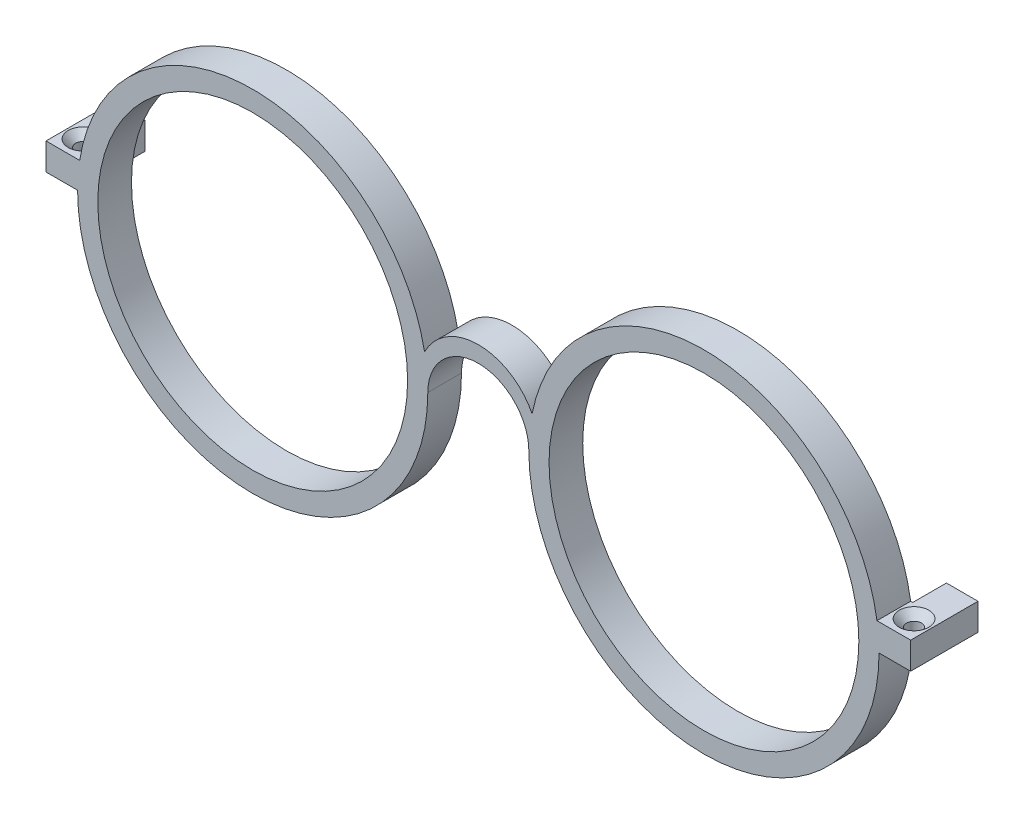
SolidWorks part; units mm, degrees
ref_plane "Ebene vorne" through (0, 0, 0) normal (0, 0, 1) x (1, 0, 0)
ref_plane "Ebene oben" through (0, 0, 0) normal (0, 1, 0) x (1, 0, 0)
ref_plane "Ebene rechts" through (0, 0, 0) normal (1, 0, 0) x (0, 0, -1)
sketch "Skizze1" plane through (0, 0, 0) normal (0, 0, 1) x (1, 0, 0)
  line L0 (59.5, 0) -> (64.1905, 0)
  line L1 (64.1905, 0) -> (64.1905, 4)
  line L2 (64.1905, 4) -> (59.1905, 4)
  line L3 (-59.5, 0) -> (-64.1905, 0)
  line L4 (-64.1905, 0) -> (-64.1905, 4)
  line L5 (-64.1905, 4) -> (-59.1905, 4)
  circle A0 centre (-33.5, 0) radius 26
  circle A1 centre (33.5, 0) radius 26
  arc A2 (-7.5, 0) -> (7.5, 0) centre (0, 0) cw
  circle A3 centre (33.5, 0) radius 23
  circle A4 centre (-33.5, 0) radius 23
  arc A5 (-7.9808, 4.9768) -> (7.9853, 5) centre (0.0081, 0.9725) cw
  dimension "D1" = 52
  dimension "D2" = 52
  dimension "D5" = 7.5
  dimension "D6" = 46
  dimension "D7" = 46
  dimension "D3" = 33.5
  dimension "D4" = 33.5
  dimension "D8" = 5
  dimension "D9" = 5
  dimension "D10" = 4
  dimension "D11" = 4
  dimension "D12" = 5
  dimension "D13" = 5
extrude "Aufsatz-Linear austragen1" add sketch "Skizze1" along normal blind 5 contours A0 A4 | A0 L5 L4 L3 | A4 | A5 A0 A2 A1 | A1 A3 | A1 L0 L1 L2
sketch "Skizze2" plane through (0, 0, 0) normal (0, 0, -1) x (-1, 0, 0)
  line L1 (-64.1905, 4) -> (-59.5, 4)
  line L2 (-64.1905, 4) -> (-64.1905, 0)
  line L3 (-64.1905, 0) -> (-59.5, 0)
  line L4 (-59.5, 4) -> (-59.5, 0)
  line L5 (64.1905, 4) -> (59.5, 4)
  line L6 (64.1905, 4) -> (64.1905, 0)
  line L7 (64.1905, 0) -> (59.5, 0)
  line L8 (59.5, 4) -> (59.5, 0)
extrude "Aufsatz-Linear austragen2" add sketch "Skizze2" along normal blind 5
hole_wizard "Formsenkung für M2 Senkschraube mit Schlitz/Kreuzschlitz1" positions "Skizze5" profile "Skizze3" countersink size "M2" standard "ANSI Metrisch"
sketch "Skizze5" plane through (0, 4, 0) normal (0, 1, 0) x (1, 0, 0)
  line L0 (-64.1905, -5) -> (-59.1905, -5) construction
  line L1 (-64.1905, -5) -> (-64.1905, 5) construction
  line L2 (64.1905, -5) -> (64.1905, 5) construction
  line L3 (64.1905, -5) -> (59.1905, -5) construction
  point P0 (61.6905, -2)
  point P2 (-61.6905, -2)
  point P21 (61.6905, -5)
  dimension "D1" = 3
  dimension "D2" = 2.5
  dimension "D3" = 2.5
  dimension "D4" = 3
sketch "Skizze3" plane through (61.6905, 4, 2) normal (1, 0, 0) x (0, 0, 1)
  line L0 (0, 0) -> (0, 50.6609)
  line L1 (0, 50.6609) -> (1.1, 50)
  line L2 (1.1, 50) -> (1.1, 1.1)
  line L3 (1.1, 1.1) -> (2.2, 0)
  line L5 (2.2, 0) -> (0, 0)
  line L6 (-1.1, 1.1) -> (-2.2, 0) construction
  line L10 (0, 50.6609) -> (-1.1, 50) construction
  line L11 (0, -6.35) -> (0, 107.95) construction
  dimension "Bohrerdurchmesser" = 2.2
  dimension "Bohrungstiefe" = 50
  dimension "Senkdurchmesser (Oben)" = 4.4
  dimension "Senkwinkel (Oben)" = 90
  dimension "Spitzenwinkel" = 118
